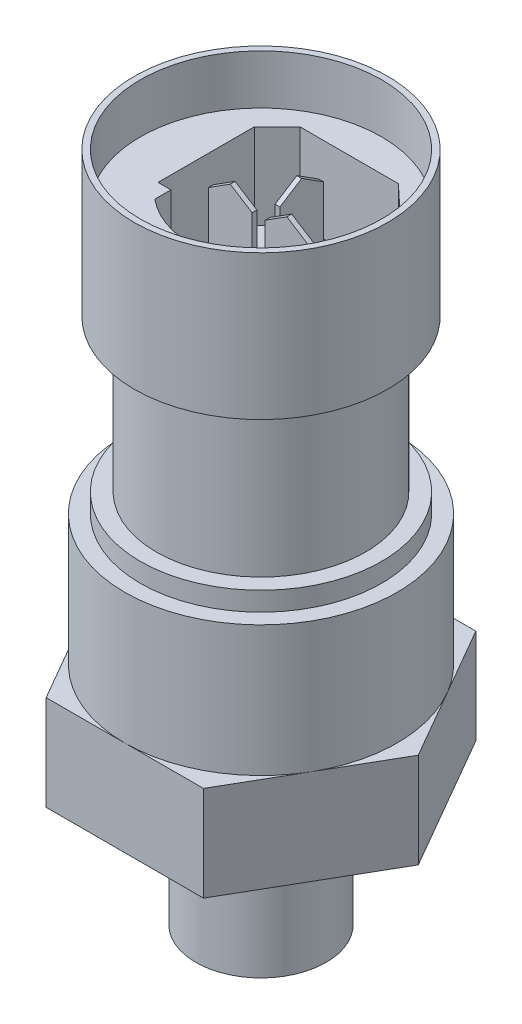
SolidWorks part; units mm, degrees
ref_plane "Front Plane" through (0, 0, 0) normal (0, 0, 1) x (1, 0, 0)
ref_plane "Top Plane" through (0, 0, 0) normal (0, 1, 0) x (1, 0, 0)
ref_plane "Right Plane" through (0, 0, 0) normal (1, 0, 0) x (0, 0, -1)
sketch "Sketch1" plane through (0, 0, 0) normal (0, 1, 0) x (1, 0, 0)
  circle A0 centre (0, 0) radius 5.1435
  dimension "D1" = 10.287
extrude "Boss-Extrude1" add sketch "Sketch1" along normal blind 10.3
sketch "Sketch2" plane through (0, 10.3, 0) normal (0, 1, 0) x (1, 0, 0)
  line L1 (6.2065, 10.75) -> (-6.2065, 10.75)
  line L2 (-6.2065, 10.75) -> (-12.413, 0)
  line L3 (-12.413, 0) -> (-6.2065, -10.75)
  line L4 (-6.2065, -10.75) -> (6.2065, -10.75)
  line L5 (6.2065, -10.75) -> (12.413, 0)
  line L6 (12.413, 0) -> (6.2065, 10.75)
  circle A0 centre (0, 0) radius 10.75 construction
  dimension "D1" = 21.5
  dimension "D2" = 21.5
extrude "Boss-Extrude2" add sketch "Sketch2" along normal blind 7.5
sketch "Sketch3" plane through (0, 17.8, 0) normal (0, 1, 0) x (1, 0, 0)
  circle A0 centre (0, 0) radius 10.75
extrude "Boss-Extrude3" add sketch "Sketch3" along normal blind 10.3
sketch "Sketch4" plane through (0, 28.1, 0) normal (0, 1, 0) x (1, 0, 0)
  circle A0 centre (0, 0) radius 9.525
  dimension "D1" = 19.05
extrude "Boss-Extrude4" add sketch "Sketch4" along normal blind 1.5
sketch "Sketch5" plane through (0, 29.6, 0) normal (0, 1, 0) x (1, 0, 0)
  circle A1 centre (0, 0) radius 8.255
  dimension "D1" = 16.51
extrude "Boss-Extrude5" add sketch "Sketch5" along normal blind 12
sketch "Sketch6" plane through (0, 41.6, 0) normal (0, 1, 0) x (1, 0, 0)
  circle A0 centre (0, 0) radius 10
  dimension "D1" = 20
extrude "Boss-Extrude6" add sketch "Sketch6" along normal blind 11.4
sketch "Sketch7" plane through (0, 0, 0) normal (0, -1, 0) x (1, 0, 0)
  circle A0 centre (0, 0) radius 4.3053
  dimension "D1" = 8.6106
extrude "Cut-Extrude1" cut sketch "Sketch7" against normal blind 11.4
thread "Thread1" pitch 1.0583 start angle 0, offset 0, length 0, pitch 0.9408, diameter 10.287
ref_plane "Plane1" through (5.1435, 0, 0) normal (0, 0, 1) x (1, 0, 0)
sketch "Thread Profile1" plane through (5.1435, 0, 0) normal (0, 0, 1) x (1, 0, 0)
  line L0 (0, 0) -> (0, 1.0583) construction
  line L11 (0, 0) -> (0, 0.926)
  line L12 (0, 0.926) -> (-0.5728, 0.5953)
  line L13 (-0.5728, 0.5953) -> (-0.5728, 0.3307)
  line L15 (-0.5728, 0.3307) -> (0, 0)
  line L17 (-0.5728, 0.463) -> (0, 0.463) construction
  point P2 (0, 0)
  dimension "Pitch" = 1.0583
  dimension "Profile_Angle" = 60
  dimension "Profile_Land" = 0.2646
  dimension "Profile_Height" = 0.5728
sketch "Sketch28" plane through (0, 0, 0) normal (0, -1, 0) x (-1, 0, 0)
  circle A0 centre (0, 0) radius 4.3053
extrude "Boss-Extrude7" add sketch "Sketch28" against normal blind 11.4
sketch "Sketch29" plane through (0, 0, 0) normal (0, -1, 0) x (1, 0, 0)
  circle A0 centre (0, 0) radius 1.5
  dimension "D1" = 3
extrude "Cut-Extrude2" cut sketch "Sketch29" against normal blind 11.4 contours A0
sketch "Sketch30" plane through (0, 53, 0) normal (0, 1, 0) x (1, 0, 0)
  circle A0 centre (0, 0) radius 9.525
  dimension "D1" = 19.05
extrude "Cut-Extrude6" cut sketch "Sketch30" against normal blind 10.638
sketch "Sketch31" plane through (0, 42.362, 0) normal (0, 1, 0) x (1, 0, 0)
  line L1 (0, 16.67) -> (0, -21.3304) construction
  line L2 (0, -21.3304) -> (0, 0) construction
  line L3 (0, 0) -> (26.7846, 0) construction
  line L4 (26.7846, 0) -> (-26.2213, 0) construction
  line L5 (-0.1905, 4.7444) -> (0.1905, 4.7444)
  line L6 (-0.1905, 4.7444) -> (-0.1905, 1.3008)
  line L7 (-0.1905, 1.3008) -> (0.1905, 1.3008)
  line L8 (0.1905, 4.7444) -> (0.1905, 1.3008)
  line L9 (-0.1905, 4.7444) -> (0.1905, 1.3008) construction
  line L10 (-0.1905, 1.3008) -> (0.1905, 4.7444) construction
  line L11 (-3.957, 0.1905) -> (-0.5134, 0.1905)
  line L12 (-3.957, 0.1905) -> (-3.957, -0.1905)
  line L13 (-3.957, -0.1905) -> (-0.5134, -0.1905)
  line L14 (-0.5134, 0.1905) -> (-0.5134, -0.1905)
  line L15 (-3.957, 0.1905) -> (-0.5134, -0.1905) construction
  line L16 (-3.957, -0.1905) -> (-0.5134, 0.1905) construction
  line L17 (0.5134, 0.1905) -> (3.957, 0.1905)
  line L18 (0.5134, 0.1905) -> (0.5134, -0.1905)
  line L19 (0.5134, -0.1905) -> (3.957, -0.1905)
  line L20 (3.957, 0.1905) -> (3.957, -0.1905)
  line L21 (0.5134, 0.1905) -> (3.957, -0.1905) construction
  line L22 (0.5134, -0.1905) -> (3.957, 0.1905) construction
  circle A0 centre (0, 0) radius 10 construction
  circle A1 centre (0, 0) radius 9.525 construction
  circle A3 centre (0, 0) radius 9.525 construction
  point P3 (0, 3.0226)
  point P11 (-2.2352, 0)
  point P16 (2.2352, 0)
  dimension "D1" = 0.381
  dimension "D2" = 0.381
  dimension "D3" = 0.381
  dimension "D4" = 2.2352
  dimension "D5" = 2.2352
  dimension "D6" = 3.0226
  dimension "D7" = 3.957
  dimension "D8" = 0.1905
  dimension "D9" = 4.7444
extrude "Boss-Extrude8" add sketch "Sketch31" along normal blind 7.239
sketch "Sketch32" plane through (0, 0, 0.1905) normal (0, 0, 1) x (1, 0, 0)
  line L0 (-2.2352, 49.601) -> (-0.5134, 48.5088) construction
  line L1 (-3.957, 49.601) -> (-0.5134, 49.601) construction
  line L2 (-0.5134, 49.601) -> (-0.5134, 42.362) construction
  line L3 (-0.5134, 48.5088) -> (-3.957, 48.5088) construction
  line L4 (-3.957, 49.601) -> (-3.957, 42.362) construction
  line L5 (-3.957, 48.5088) -> (-2.2352, 49.601) construction
  line L6 (-2.2352, 49.601) -> (-3.957, 48.5088)
  line L7 (-3.957, 48.5088) -> (-0.5134, 48.5088)
  line L8 (-0.5134, 48.5088) -> (-2.2352, 49.601)
  line L10 (-3.957, 42.362) -> (-0.5134, 42.362)
  line L11 (-0.5134, 42.362) -> (-0.5134, 49.601)
  line L12 (-0.5134, 49.601) -> (-3.957, 49.601)
  line L13 (-3.957, 49.601) -> (-3.957, 42.362)
  line L14 (-3.957, 42.362) -> (-0.5134, 42.362)
  line L15 (-0.5134, 42.362) -> (-0.5134, 49.601)
  line L16 (-0.5134, 49.601) -> (-3.957, 49.601)
  line L17 (-3.957, 49.601) -> (-3.957, 42.362)
  line M7 (-0.5134, 42.362) -> (-0.5134, 49.601)
  line M8 (-0.5134, 49.601) -> (-3.957, 49.601)
  line M9 (-3.957, 49.601) -> (-3.957, 42.362)
  dimension "D1" = 1.0922
  dimension "D2" = 0
extrude "Cut-Extrude7" cut sketch "Sketch32" against normal blind 6.731 contours L6 M8 M9 | L8 M7 M8
sketch "Sketch33" plane through (0, 0, 0.1905) normal (0, 0, 1) x (1, 0, 0)
  line L0 (2.2352, 49.601) -> (3.957, 48.5088) construction
  line L1 (0.5134, 49.601) -> (3.957, 49.601) construction
  line L2 (3.957, 49.601) -> (3.957, 42.362) construction
  line L3 (3.957, 48.5088) -> (0.5134, 48.5088) construction
  line L4 (0.5134, 49.601) -> (0.5134, 42.362) construction
  line L5 (0.5134, 48.5088) -> (2.2352, 49.601) construction
  line L6 (2.2352, 49.601) -> (3.957, 48.5088)
  line L7 (3.957, 48.5088) -> (0.5134, 48.5088)
  line L8 (0.5134, 48.5088) -> (2.2352, 49.601)
  line L13 (0.5134, 42.362) -> (3.957, 42.362)
  line L14 (3.957, 42.362) -> (3.957, 49.601)
  line L15 (3.957, 49.601) -> (0.5134, 49.601)
  line L16 (0.5134, 49.601) -> (0.5134, 42.362)
  line L17 (0.5134, 42.362) -> (3.957, 42.362)
  line L18 (3.957, 42.362) -> (3.957, 49.601)
  line L19 (3.957, 49.601) -> (0.5134, 49.601)
  line L20 (0.5134, 49.601) -> (0.5134, 42.362)
  line M10 (3.957, 42.362) -> (3.957, 49.601)
  line M11 (3.957, 49.601) -> (0.5134, 49.601)
  line M12 (0.5134, 49.601) -> (0.5134, 42.362)
  dimension "D1" = 1.0922
  dimension "D2" = 0
extrude "Cut-Extrude8" cut sketch "Sketch33" against normal blind 1.651 contours L8 M12 M11 | L6 M11 M10
sketch "Sketch34" plane through (0.1905, 0, 0) normal (1, 0, 0) x (0, 0, -1)
  line L0 (3.0226, 49.601) -> (4.7444, 48.5088)
  line L1 (1.3008, 49.601) -> (4.7444, 49.601) construction
  line L2 (4.7444, 49.601) -> (4.7444, 42.362) construction
  line L3 (4.7444, 48.5088) -> (1.3008, 48.5088)
  line L4 (1.3008, 49.601) -> (1.3008, 42.362) construction
  line L5 (1.3008, 48.5088) -> (3.0226, 49.601)
  line L10 (1.3008, 42.362) -> (4.7444, 42.362)
  line L11 (4.7444, 42.362) -> (4.7444, 49.601)
  line L12 (4.7444, 49.601) -> (1.3008, 49.601)
  line L13 (1.3008, 49.601) -> (1.3008, 42.362)
  line L14 (1.3008, 42.362) -> (4.7444, 42.362)
  line L15 (4.7444, 42.362) -> (4.7444, 49.601)
  line L16 (4.7444, 49.601) -> (1.3008, 49.601)
  line L17 (1.3008, 49.601) -> (1.3008, 42.362)
  line M9 (4.7444, 42.362) -> (4.7444, 49.601)
  line M10 (4.7444, 49.601) -> (1.3008, 49.601)
  line M11 (1.3008, 49.601) -> (1.3008, 42.362)
  dimension "D1" = 1.0922
  dimension "D2" = 0
extrude "Cut-Extrude9" cut sketch "Sketch34" against normal blind 1.651 contours L5 M11 M10 | L0 M10 M9
sketch "Sketch35" plane through (0, 42.362, 0) normal (0, 1, 0) x (1, 0, 0)
  line L0 (-3.9189, 6.985) -> (-5.715, 5.1889)
  line L1 (3.0134, -3.683) -> (4.3631, -3.683)
  line L2 (-5.715, -2.413) -> (-5.715, 5.1889)
  line L3 (-3.9189, 6.985) -> (3.8604, 6.985)
  line L4 (5.715, -2.413) -> (5.715, 5.2423)
  line L5 (-4.699, -5.7432) -> (4.9089, 5.9998) construction
  line L6 (-4.9068, 5.9972) -> (4.3631, -5.3326) construction
  line L7 (3.8604, 6.985) -> (5.715, 5.2423)
  line L8 (-5.715, -2.413) -> (-4.699, -2.413)
  line L9 (-4.699, -2.413) -> (-4.699, -3.683)
  line L10 (5.715, -2.413) -> (4.3631, -2.413)
  line L11 (4.3631, -2.413) -> (4.3631, -3.683)
  arc A0 (-4.699, -3.683) -> (4.3631, -3.683) centre (-0.168, 1.7488) ccw
  circle A1 centre (0, 0) radius 9.525
  circle A2 centre (0, 0) radius 9.525
  circle A3 centre (0, 0) radius 10.75 construction
  point P0 (0, 0)
  circle M12 centre (0, 0) radius 9.525
  dimension "D15" = 1.7568
  dimension "D16" = 7.0735
  dimension "D2" = 7.6019
  dimension "D3" = 7.7487
  dimension "D4" = 5.9998
  dimension "D5" = 6.985
  dimension "D6" = 1.27
  dimension "D7" = 1.016
  dimension "D8" = 1.3519
  dimension "D9" = 9.0621
  dimension "D10" = 2.54
  dimension "D11" = 2.5449
  dimension "D12" = 7.6553
  dimension "D13" = 3.683
  dimension "D14" = 5.715
  dimension "D1" = 0
extrude "Boss-Extrude9" add sketch "Sketch35" along normal blind 6.731 contours A0 L9 L8 L2 L0 L3 L7 L4 L10 L11 M12
